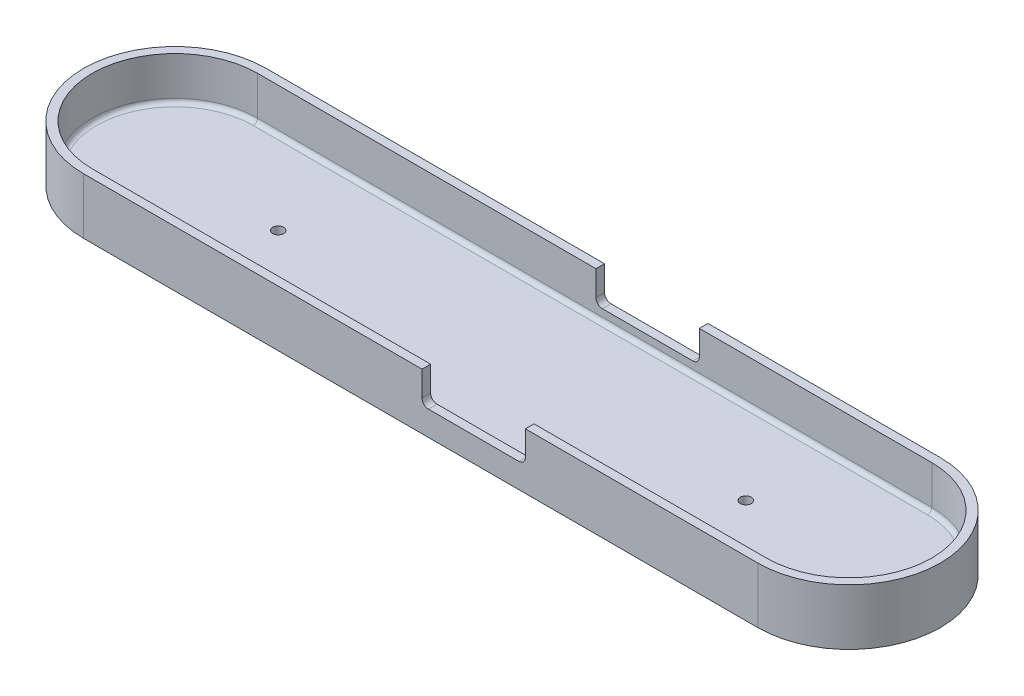
SolidWorks part; units mm, degrees
material "PLA"
ref_plane "Front Plane" through (0, 0, 0) normal (0, 0, 1) x (1, 0, 0)
ref_plane "Top Plane" through (0, 0, 0) normal (0, 1, 0) x (1, 0, 0)
ref_plane "Right Plane" through (0, 0, 0) normal (1, 0, 0) x (0, 0, -1)
sketch "Sketch1" plane through (0, 0, 0) normal (0, 1, 0) x (1, 0, 0)
  line L0 (-99.441, 0) -> (99.441, 0) construction
  line L1 (0, -55.9739) -> (0, 55.9739) construction
  line L2 (-99.441, 24.384) -> (99.441, 24.384)
  line L3 (-99.441, -24.384) -> (99.441, -24.384)
  arc A0 (-99.441, 24.384) -> (-99.441, -24.384) centre (-99.441, 0) ccw
  arc A1 (99.441, 24.384) -> (99.441, -24.384) centre (99.441, 0) cw
  circle A2 centre (-99.441, 0) radius 24.13 construction
  point P4 (0, 0)
  point P10 (0, 0)
  dimension "D2" = 0.254
  dimension "D3" = 48.26
  dimension "D1" = 198.882
extrude "MainBlock" add sketch "Sketch1" along normal blind 3.81
sketch "Sketch2" plane through (0, 0, 0) normal (0, -1, 0) x (1, 0, 0)
  line L0 (0, 0) -> (0, 50000) construction
  line L1 (-99.441, 26.924) -> (99.441, 26.924)
  line L2 (-99.441, -24.384) -> (99.441, -24.384)
  line L3 (99.441, 24.384) -> (-99.441, 24.384)
  line L5 (99.441, 24.384) -> (-99.441, 24.384)
  line L6 (-95.25, 0) -> (49904.75, 0) construction
  line L7 (99.441, -24.384) -> (-99.441, -24.384)
  line L8 (-99.441, -26.924) -> (99.441, -26.924)
  arc A0 (-99.441, 26.924) -> (-99.441, -26.924) centre (-99.441, 0) ccw
  arc A1 (99.441, 24.384) -> (99.441, -24.384) centre (99.441, 0) cw
  arc A2 (-99.441, 24.384) -> (-99.441, -24.384) centre (-99.441, 0) ccw
  arc A3 (99.441, -24.384) -> (99.441, 24.384) centre (99.441, 0) ccw
  arc A4 (-99.441, 24.384) -> (-99.441, -24.384) centre (-99.441, 0) ccw
  arc A6 (99.441, 26.924) -> (99.441, -26.924) centre (99.441, 0) cw
  point P0 (0, 24.384)
  point P15 (0, 26.924)
  point P16 (0, -24.384)
  point P19 (0, -26.924)
  dimension "D2" = 2.54
  dimension "D1" = 0
extrude "Boss-Extrude1" add sketch "Sketch2" against normal blind 16.51
sketch "Sketch3" plane through (0, 0, 0) normal (0, -1, 0) x (1, 0, 0)
  line L0 (0, 0) -> (50000, 0) construction
  line L1 (0, 0) -> (0, 50000) construction
  circle A1 centre (0, 0) radius 1.6256 construction
  circle A8 centre (-68.961, 0) radius 1.6256
  circle A9 centre (68.961, 0) radius 1.6256
  arc A10 (99.441, -26.924) -> (99.441, 26.924) centre (99.441, 0) ccw construction
  arc A11 (-99.441, 26.924) -> (-99.441, -26.924) centre (-99.441, 0) ccw construction
  arc A12 (99.441, -26.924) -> (99.441, 26.924) centre (99.441, 0) ccw construction
  arc A13 (-99.441, 26.924) -> (-99.441, -26.924) centre (-99.441, 0) ccw construction
  dimension "0.085" = 3.2512
  dimension "D2" = 3.2512
  dimension "D3" = 3.2512
  dimension "D4" = 30.48
  dimension "D5" = 30.48
extrude "Cut-Extrude1" cut sketch "Sketch3" against normal through all
fillet "Fillet1" radius 1.27 4 edges at (123.825, 3.81, 0) (0, 3.81, 24.384) (-123.825, 3.81, 0) (0, 3.81, -24.384)
sketch "Sketch4" plane through (0, 16.51, 0) normal (0, 1, 0) x (1, 0, 0)
  line L0 (0.381, 26.924) -> (0.381, 24.384)
  line L1 (-99.441, 26.924) -> (99.441, 26.924) construction
  line L2 (0.381, 24.384) -> (30.861, 24.384)
  line L3 (-99.441, 24.384) -> (99.441, 24.384) construction
  line L4 (30.861, 24.384) -> (30.861, 26.924)
  line L5 (30.861, 26.924) -> (0.381, 26.924)
  line L6 (15.621, 26.924) -> (15.621, 24.384) construction
  line L7 (99.441, 0) -> (99.441, 24.384) construction
  arc A1 (99.441, -24.384) -> (99.441, 24.384) centre (99.441, 0) ccw construction
  arc A2 (99.441, -24.384) -> (99.441, 24.384) centre (99.441, 0) ccw construction
  dimension "D2" = 83.82
  dimension "D1" = 30.48
extrude "Stabilizer-Mount-Cutout" cut sketch "Sketch4" against normal blind 9.271
mirror "Mirror1" about plane through (0, 0, 0) normal (0, 0, 1) of "Stabilizer-Mount-Cutout"
fillet "Fillet2" radius 1.905 4 edges at (0.381, 7.239, -25.654) (30.861, 7.239, -25.654) (0.381, 7.239, 25.654) (30.861, 7.239, 25.654)
equation "\"D2@Sketch3\"=\"0.085@Sketch3\""
equation "\"D3@Sketch3\"=\"0.085@Sketch3\""
